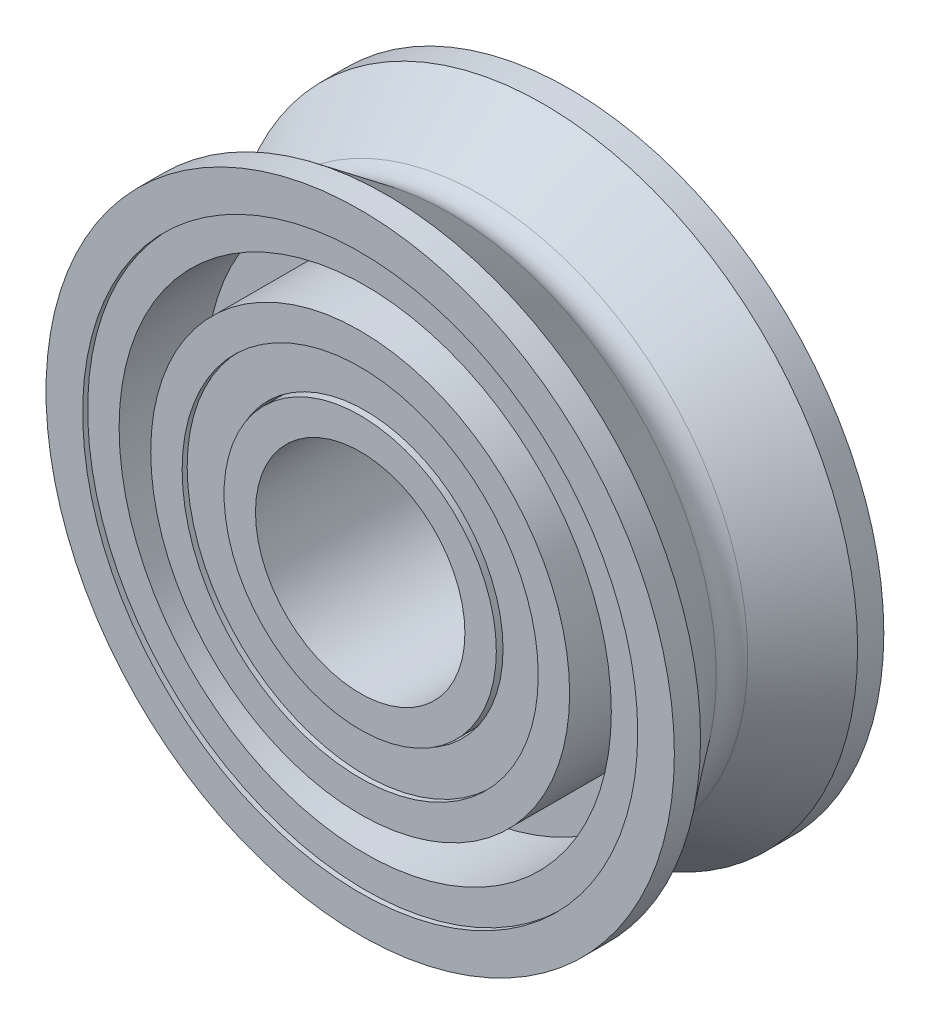
SolidWorks part; units mm, degrees
ref_plane "Front" through (0, 0, 0) normal (0, 0, 1) x (1, 0, 0)
ref_plane "Top" through (0, 0, 0) normal (0, 1, 0) x (1, 0, 0)
ref_plane "Right" through (0, 0, 0) normal (1, 0, 0) x (0, 0, -1)
sketch "Sketch1" plane through (0, 0, 0) normal (1, 0, 0) x (0, 0, -1)
  line L0 (1.1906, 4.7625) -> (1.5875, 4.7625)
  line L1 (-1.1906, 4.7625) -> (-1.5875, 4.7625)
  line L2 (-1.1906, 4.7625) -> (-0.2381, 4.0481)
  line L3 (1.5113, 2.6988) -> (1.5113, 2.0637)
  line L4 (1.5875, 1.5875) -> (-1.5875, 1.5875)
  line L5 (-1.5113, 2.0638) -> (-1.5113, 2.6988)
  line L6 (1.1906, 4.7625) -> (0.2381, 4.0481)
  line L7 (-1.5875, 4.2069) -> (-1.5113, 4.2069)
  line L8 (-1.5875, 0) -> (1.5875, 0) construction
  line L9 (-1.5113, 4.2069) -> (-1.5113, 3.7306)
  line L10 (1.5875, 4.7625) -> (1.5875, 4.2069)
  line L11 (1.5875, 4.2069) -> (1.5113, 4.2069)
  line L12 (-1.5113, 2.0638) -> (-1.5875, 2.0638)
  line L13 (-1.5875, 2.0638) -> (-1.5875, 1.5875)
  line L14 (0, 3.9688) -> (0, -3.9688) construction
  line L15 (1.5875, 2.0637) -> (1.5113, 2.0637)
  line L16 (1.5875, 2.0637) -> (1.5875, 1.5875)
  line L17 (-1.5875, 4.7625) -> (-1.5875, -4.7625) construction
  line L18 (-1.5113, 3.7306) -> (-0.1984, 3.7306)
  line L19 (-0.1984, 3.7306) -> (-0.1984, 3.175)
  line L20 (-0.1984, 3.175) -> (-1.5875, 3.175)
  line L21 (-1.5875, 4.2069) -> (-1.5875, 4.7625)
  line L22 (1.5113, 3.7306) -> (0.1984, 3.7306)
  line L23 (0.1984, 3.7306) -> (0.1984, 3.175)
  line L24 (0.1984, 3.175) -> (1.5875, 3.175)
  line L25 (1.5113, 4.2069) -> (1.5113, 3.7306)
  line L26 (-1.5113, 2.6988) -> (-1.5875, 2.6988)
  line L27 (-1.5875, 2.6988) -> (-1.5875, 3.175)
  line L28 (1.5875, 3.175) -> (1.5875, 2.6988)
  line L29 (1.5875, 2.6988) -> (1.5113, 2.6988)
  arc A0 (-0.2381, 4.0481) -> (0.2381, 4.0481) centre (0, 4.3656) ccw
  circle A1 centre (0, 4.3656) radius 0.3969 construction
  circle A2 centre (0, 0) radius 1.5875 construction
  circle A3 centre (0, 0) radius 2.0638 construction
  circle A4 centre (0, 0) radius 3.175 construction
  circle A5 centre (0, -4.3656) radius 0.3969 construction
  point P28 (-1.5875, 0)
  dimension "Rope Dia" = 0.7937
  dimension "Shaft Dia" = 3.175
  dimension "D1" = 4.1275
  dimension "D3" = 6.35
  dimension "Wd" = 3.175
  dimension "D8" = 0.3969
  dimension "Groove Dia" = 7.9375
  dimension "OD" = 9.525
  dimension "D6" = 0.0762
  dimension "D2" = 0.3969
revolve "Revolve1" add sketch "Sketch1" angle 360 about L8
sketch "Sketch2" plane through (0, 0, 0) normal (0, 0, 1) x (1, 0, 0)
  circle A0 centre (0, 0) radius 2.0638 construction
  circle A1 centre (0, 0) radius 2.0638
extrude "Cut-Extrude-Thin1" cut sketch "Sketch2" against normal through all and the other way through all thin
equation "\"D1@Sketch1\" = \"Shaft Dia@Sketch1\" * 1.3"
equation "\"D3@Sketch1\" = \"Shaft Dia@Sketch1\" * 2"
equation "\"D8@Sketch1\" = \"Wd@Sketch1\" * .125"
equation "\"D2@Sketch1\" = \"D8@Sketch1\""
